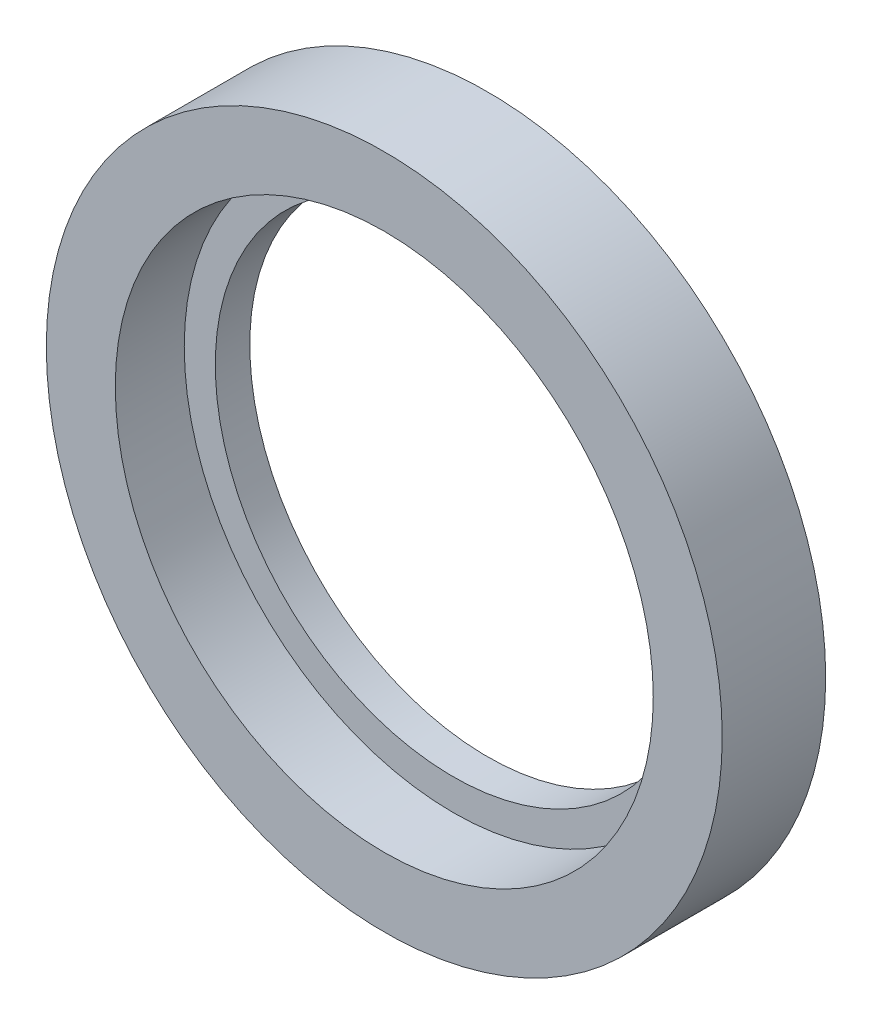
SolidWorks part; units mm, degrees
ref_plane "Płaszczyzna przednia" through (0, 0, 0) normal (0, 0, 1) x (1, 0, 0)
ref_plane "Płaszczyzna górna" through (0, 0, 0) normal (0, 1, 0) x (1, 0, 0)
ref_plane "Płaszczyzna prawa" through (0, 0, 0) normal (1, 0, 0) x (0, 0, -1)
sketch "Szkic1" plane through (0, 0, 0) normal (0, 0, 1) x (1, 0, 0)
  circle A1 centre (0, 0) radius 49
  circle A2 centre (0, 0) radius 34.5
  dimension "D1" = 69
  dimension "D2" = 98
extrude "Dodanie-wyciągnięcie1" add sketch "Szkic1" along normal blind 15
sketch "Szkic2" plane through (0, 0, 0) normal (0, 0, -1) x (-1, 0, 0)
  circle A0 centre (44, 0) radius 3.3
  point P2 (37.6199, 5.3613)
  dimension "D1" = 6.6
  dimension "D2" = 44
  dimension "D3" = 0
extrude "Wytnij-wyciągnięcie1" cut sketch "Szkic2" against normal blind 6
pattern_circular "Szyk kołowy1" count 6 every 60 about axis through (0, 0, 0) along (0, 0, 1) of "Wytnij-wyciągnięcie1"
sketch "Szkic3" plane through (0, 0, 15) normal (0, 0, 1) x (1, 0, 0)
  circle A0 centre (0, 0) radius 39
  dimension "D1" = 78
extrude "Wytnij-wyciągnięcie2" cut sketch "Szkic3" against normal blind 10
